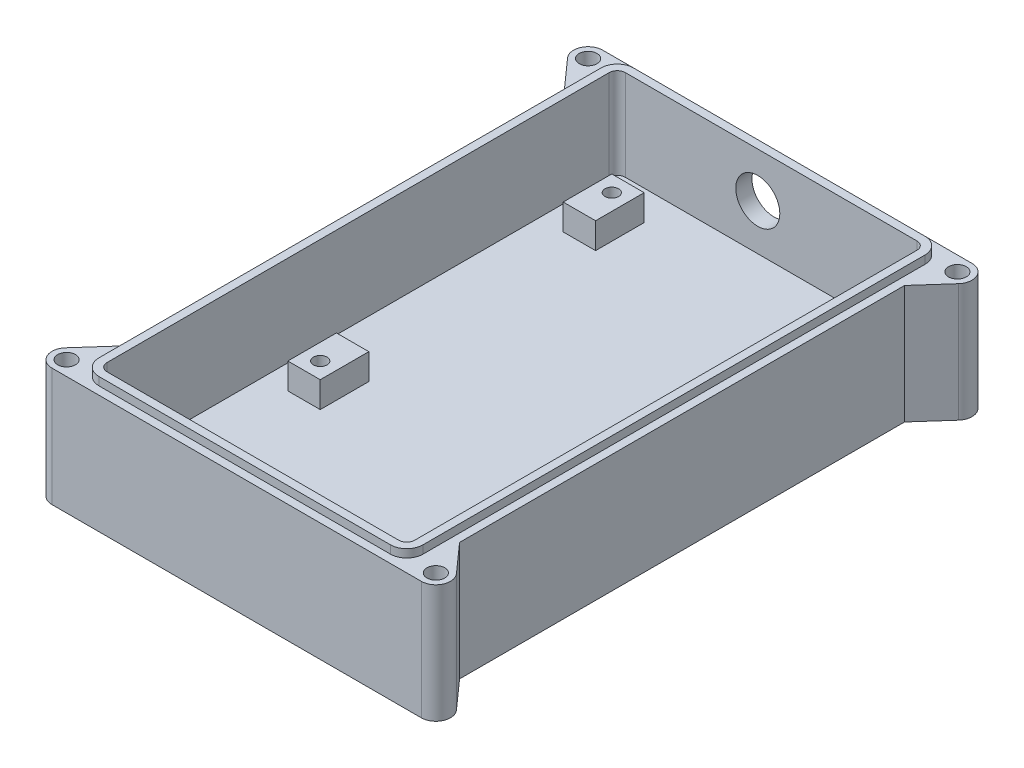
SolidWorks part; units mm, degrees
ref_plane "Alzado" through (0, 0, 0) normal (0, 0, 1) x (1, 0, 0)
ref_plane "Planta" through (0, 0, 0) normal (0, 1, 0) x (1, 0, 0)
ref_plane "Vista lateral" through (0, 0, 0) normal (1, 0, 0) x (0, 0, -1)
sketch "Croquis1" plane through (0, 0, 0) normal (0, 1, 0) x (1, 0, 0)
  line L0 (-45, 80) -> (45, 80)
  line L1 (-47.5, -80) -> (47.5, -80) construction
  line L2 (-47.5, -80) -> (-47.5, 80) construction
  line L3 (-47.5, 80) -> (47.5, 80) construction
  line L4 (47.5, -80) -> (47.5, 80) construction
  line L5 (-47.5, -80) -> (47.5, 80) construction
  line L6 (-47.5, 80) -> (47.5, -80) construction
  line L7 (-47.5, 77.5) -> (-47.5, -77.5)
  line L8 (-45, -80) -> (45, -80)
  line L9 (47.5, -77.5) -> (47.5, 77.5)
  line L10 (-45, 85) -> (45, 85)
  line L11 (52.5, -77.5) -> (52.5, 77.5)
  line L12 (-45, -85) -> (45, -85)
  line L13 (-52.5, 77.5) -> (-52.5, -77.5)
  line L14 (-45, 82.5) -> (45, 82.5)
  line L15 (50, -77.5) -> (50, 77.5)
  line L16 (-45, -82.5) -> (45, -82.5)
  line L17 (-50, 77.5) -> (-50, -77.5)
  circle A0 centre (-45, 77.5) radius 2.5 construction
  circle A1 centre (45, 77.5) radius 2.5 construction
  circle A2 centre (-45, -77.5) radius 2.5 construction
  circle A3 centre (45, -77.5) radius 2.5 construction
  arc A5 (47.5, 77.5) -> (45, 80) centre (45, 77.5) ccw
  arc A6 (-45, 80) -> (-47.5, 77.5) centre (-45, 77.5) ccw
  arc A7 (-47.5, -77.5) -> (-45, -80) centre (-45, -77.5) ccw
  arc A8 (45, -80) -> (47.5, -77.5) centre (45, -77.5) ccw
  arc A9 (52.5, 77.5) -> (45, 85) centre (45, 77.5) ccw
  arc A10 (45, -85) -> (52.5, -77.5) centre (45, -77.5) ccw
  arc A11 (-52.5, -77.5) -> (-45, -85) centre (-45, -77.5) ccw
  arc A12 (-45, 85) -> (-52.5, 77.5) centre (-45, 77.5) ccw
  arc A13 (50, 77.5) -> (45, 82.5) centre (45, 77.5) ccw
  arc A14 (45, -82.5) -> (50, -77.5) centre (45, -77.5) ccw
  arc A15 (-50, -77.5) -> (-45, -82.5) centre (-45, -77.5) ccw
  arc A16 (-45, 82.5) -> (-50, 77.5) centre (-45, 77.5) ccw
  point P0 (0, 0)
  dimension "D3" = 5
  dimension "D4" = 5
  dimension "D5" = 5
  dimension "D6" = 5
  dimension "D1" = 95
  dimension "D2" = 160
  dimension "D7" = 5
  dimension "D8" = 2.5
extrude "Saliente-Extruir2" add sketch "Croquis1" along normal blind 11 contours L8 A8 L9 A5 L0 A6 L7 A7 | L10 A12 L13 A11 L12 A10 L11 A9 A16 L14 A13 L15 A14 L16 A15 L17 | L14 A16 L17 A15 L16 A14 L15 A13 A8 L8 A7 L7 A6 L0 A5 L9
sketch "Croquis2" plane through (0, 11, 0) normal (0, 1, 0) x (1, 0, 0)
  line L4 (45, 85) -> (-45, 85)
  line L5 (-52.5, 77.5) -> (-52.5, -77.5)
  line L6 (-45, -85) -> (45, -85)
  line L7 (52.5, -77.5) -> (52.5, 77.5)
  line L8 (45, 85) -> (-45, 85)
  line L9 (-52.5, 77.5) -> (-52.5, -77.5)
  line L10 (-45, -85) -> (45, -85)
  line L11 (52.5, -77.5) -> (52.5, 77.5)
  line L12 (47.5, -77.5) -> (47.5, 77.5)
  line L13 (-45, -80) -> (45, -80)
  line L14 (-47.5, 77.5) -> (-47.5, -77.5)
  line L15 (45, 80) -> (-45, 80)
  line L16 (47.5, -77.5) -> (47.5, 77.5)
  line L17 (-45, -80) -> (45, -80)
  line L18 (-47.5, 77.5) -> (-47.5, -77.5)
  line L19 (45, 80) -> (-45, 80)
  line L20 (45, 82.5) -> (-45, 82.5)
  line L21 (50, -77.5) -> (50, 77.5)
  line L22 (-45, -82.5) -> (45, -82.5)
  line L23 (-50, 77.5) -> (-50, -77.5)
  line L24 (45, 82.5) -> (-45, 82.5)
  line L25 (50, -77.5) -> (50, 77.5)
  line L26 (-45, -82.5) -> (45, -82.5)
  line L27 (-50, 77.5) -> (-50, -77.5)
  line L28 (45, 85) -> (-45, 85)
  line L29 (52.5, -77.5) -> (52.5, 77.5)
  line L30 (-45, -85) -> (45, -85)
  line L31 (-52.5, 77.5) -> (-52.5, -77.5)
  line L32 (45, 85) -> (-45, 85)
  line L33 (52.5, -77.5) -> (52.5, 77.5)
  line L34 (-45, -85) -> (45, -85)
  line L35 (-52.5, 77.5) -> (-52.5, -77.5)
  arc A4 (-45, 85) -> (-52.5, 77.5) centre (-45, 77.5) ccw
  arc A5 (-52.5, -77.5) -> (-45, -85) centre (-45, -77.5) ccw
  arc A6 (45, -85) -> (52.5, -77.5) centre (45, -77.5) ccw
  arc A7 (52.5, 77.5) -> (45, 85) centre (45, 77.5) ccw
  arc A8 (-45, 85) -> (-52.5, 77.5) centre (-45, 77.5) ccw
  arc A9 (-52.5, -77.5) -> (-45, -85) centre (-45, -77.5) ccw
  arc A10 (45, -85) -> (52.5, -77.5) centre (45, -77.5) ccw
  arc A11 (52.5, 77.5) -> (45, 85) centre (45, 77.5) ccw
  arc A12 (47.5, 77.5) -> (45, 80) centre (45, 77.5) ccw
  arc A13 (45, -80) -> (47.5, -77.5) centre (45, -77.5) ccw
  arc A14 (-47.5, -77.5) -> (-45, -80) centre (-45, -77.5) ccw
  arc A15 (-45, 80) -> (-47.5, 77.5) centre (-45, 77.5) ccw
  arc A16 (47.5, 77.5) -> (45, 80) centre (45, 77.5) ccw
  arc A17 (45, -80) -> (47.5, -77.5) centre (45, -77.5) ccw
  arc A18 (-47.5, -77.5) -> (-45, -80) centre (-45, -77.5) ccw
  arc A19 (-45, 80) -> (-47.5, 77.5) centre (-45, 77.5) ccw
  arc A20 (50, 77.5) -> (45, 82.5) centre (45, 77.5) ccw
  arc A21 (45, -82.5) -> (50, -77.5) centre (45, -77.5) ccw
  arc A22 (-50, -77.5) -> (-45, -82.5) centre (-45, -77.5) ccw
  arc A23 (-45, 82.5) -> (-50, 77.5) centre (-45, 77.5) ccw
  arc A24 (50, 77.5) -> (45, 82.5) centre (45, 77.5) ccw
  arc A25 (45, -82.5) -> (50, -77.5) centre (45, -77.5) ccw
  arc A26 (-50, -77.5) -> (-45, -82.5) centre (-45, -77.5) ccw
  arc A27 (-45, 82.5) -> (-50, 77.5) centre (-45, 77.5) ccw
  arc A28 (-45, 85) -> (-52.5, 77.5) centre (-45, 77.5) ccw
  arc A29 (52.5, 77.5) -> (45, 85) centre (45, 77.5) ccw
  arc A30 (45, -85) -> (52.5, -77.5) centre (45, -77.5) ccw
  arc A31 (-52.5, -77.5) -> (-45, -85) centre (-45, -77.5) ccw
  arc A32 (-45, 85) -> (-52.5, 77.5) centre (-45, 77.5) ccw
  arc A33 (52.5, 77.5) -> (45, 85) centre (45, 77.5) ccw
  arc A34 (45, -85) -> (52.5, -77.5) centre (45, -77.5) ccw
  arc A35 (-52.5, -77.5) -> (-45, -85) centre (-45, -77.5) ccw
  line M33 (45, 85) -> (-45, 85)
  arc M34 (-45, 85) -> (-52.5, 77.5) centre (-45, 77.5) ccw
  line M35 (-52.5, 77.5) -> (-52.5, -77.5)
  arc M36 (-52.5, -77.5) -> (-45, -85) centre (-45, -77.5) ccw
  line M37 (-45, -85) -> (45, -85)
  arc M38 (45, -85) -> (52.5, -77.5) centre (45, -77.5) ccw
  line M39 (52.5, -77.5) -> (52.5, 77.5)
  arc M40 (52.5, 77.5) -> (45, 85) centre (45, 77.5) ccw
  dimension "D1" = 0
  dimension "D2" = 0
  dimension "D3" = 0
  dimension "D4" = 0
extrude "Saliente-Extruir3" add sketch "Croquis2" along normal blind 25.5 contours A27 L24 A24 L25 A25 L26 A26 L27 M40 M33 M34 M35 M36 M37 M38 M39 | L24 A27 L27 A26 L26 A25 L25 A24 A19 L19 A16 L16 A17 L17 A18 L18
sketch "Croquis3" plane through (0, 36.5, 0) normal (0, 1, 0) x (1, 0, 0)
  line L4 (47.5, -77.5) -> (47.5, 77.5)
  line L5 (-45, -80) -> (45, -80)
  line L6 (-47.5, 77.5) -> (-47.5, -77.5)
  line L7 (45, 80) -> (-45, 80)
  line L8 (47.5, -77.5) -> (47.5, 77.5)
  line L9 (-45, -80) -> (45, -80)
  line L10 (-47.5, 77.5) -> (-47.5, -77.5)
  line L11 (45, 80) -> (-45, 80)
  line L12 (45, 82.5) -> (-45, 82.5)
  line L13 (50, -77.5) -> (50, 77.5)
  line L14 (-45, -82.5) -> (45, -82.5)
  line L15 (-50, 77.5) -> (-50, -77.5)
  line L16 (45, 82.5) -> (-45, 82.5)
  line L17 (50, -77.5) -> (50, 77.5)
  line L18 (-45, -82.5) -> (45, -82.5)
  line L19 (-50, 77.5) -> (-50, -77.5)
  line L20 (45, 85) -> (-45, 85)
  line L21 (52.5, -77.5) -> (52.5, 77.5)
  line L22 (-45, -85) -> (45, -85)
  line L23 (-52.5, 77.5) -> (-52.5, -77.5)
  line L24 (45, 85) -> (-45, 85)
  line L25 (52.5, -77.5) -> (52.5, 77.5)
  line L26 (-45, -85) -> (45, -85)
  line L27 (-52.5, 77.5) -> (-52.5, -77.5)
  arc A4 (47.5, 77.5) -> (45, 80) centre (45, 77.5) ccw
  arc A5 (45, -80) -> (47.5, -77.5) centre (45, -77.5) ccw
  arc A6 (-47.5, -77.5) -> (-45, -80) centre (-45, -77.5) ccw
  arc A7 (-45, 80) -> (-47.5, 77.5) centre (-45, 77.5) ccw
  arc A8 (47.5, 77.5) -> (45, 80) centre (45, 77.5) ccw
  arc A9 (45, -80) -> (47.5, -77.5) centre (45, -77.5) ccw
  arc A10 (-47.5, -77.5) -> (-45, -80) centre (-45, -77.5) ccw
  arc A11 (-45, 80) -> (-47.5, 77.5) centre (-45, 77.5) ccw
  arc A12 (50, 77.5) -> (45, 82.5) centre (45, 77.5) ccw
  arc A13 (45, -82.5) -> (50, -77.5) centre (45, -77.5) ccw
  arc A14 (-50, -77.5) -> (-45, -82.5) centre (-45, -77.5) ccw
  arc A15 (-45, 82.5) -> (-50, 77.5) centre (-45, 77.5) ccw
  arc A16 (50, 77.5) -> (45, 82.5) centre (45, 77.5) ccw
  arc A17 (45, -82.5) -> (50, -77.5) centre (45, -77.5) ccw
  arc A18 (-50, -77.5) -> (-45, -82.5) centre (-45, -77.5) ccw
  arc A19 (-45, 82.5) -> (-50, 77.5) centre (-45, 77.5) ccw
  arc A20 (-45, 85) -> (-52.5, 77.5) centre (-45, 77.5) ccw
  arc A21 (52.5, 77.5) -> (45, 85) centre (45, 77.5) ccw
  arc A22 (45, -85) -> (52.5, -77.5) centre (45, -77.5) ccw
  arc A23 (-52.5, -77.5) -> (-45, -85) centre (-45, -77.5) ccw
  arc A24 (-45, 85) -> (-52.5, 77.5) centre (-45, 77.5) ccw
  arc A25 (52.5, 77.5) -> (45, 85) centre (45, 77.5) ccw
  arc A26 (45, -85) -> (52.5, -77.5) centre (45, -77.5) ccw
  arc A27 (-52.5, -77.5) -> (-45, -85) centre (-45, -77.5) ccw
  arc M33 (-47.5, 77.5) -> (-45, 80) centre (-45, 77.5) cw
  line M34 (-45, 80) -> (45, 80)
  arc M35 (45, 80) -> (47.5, 77.5) centre (45, 77.5) cw
  line M36 (47.5, 77.5) -> (47.5, -77.5)
  arc M37 (47.5, -77.5) -> (45, -80) centre (45, -77.5) cw
  line M38 (45, -80) -> (-45, -80)
  arc M39 (-45, -80) -> (-47.5, -77.5) centre (-45, -77.5) cw
  line M40 (-47.5, -77.5) -> (-47.5, 77.5)
  dimension "D1" = 0
  dimension "D2" = 0
  dimension "D3" = 0
extrude "Saliente-Extruir4" add sketch "Croquis3" along normal blind 2.5 contours L16 A19 L19 A18 L18 A17 L17 A16 M40 M33 M34 M35 M36 M37 M38 M39
sketch "Croquis4" plane through (0, 0, 0) normal (0, -1, 0) x (1, 0, 0)
  line L0 (-45, 85) -> (57, 85)
  line L1 (57, 85) -> (-45, 85)
  line L2 (-45, 80) -> (45, 80) construction
  line L3 (52.5, 77.5) -> (52.5, -77.5) construction
  line L4 (47.5, -77.5) -> (47.5, 77.5) construction
  line L5 (-45, 80) -> (45, 80)
  line L6 (52.5, 68.6869) -> (60.3595, 77.5061)
  line L7 (47.5, -77.5) -> (47.5, 77.5)
  line L8 (52.5, 68.6869) -> (48.6887, 68.6869)
  line L9 (48.6887, 68.6869) -> (48.6887, 66.4004)
  line L10 (48.6887, 66.4004) -> (43.3926, 66.4004)
  line L11 (43.3926, 66.4004) -> (43.3926, 85)
  circle A0 centre (57, 80.5) radius 2.75 construction
  circle A1 centre (57, 80.5) radius 4.5
  arc A2 (47.5, 77.5) -> (45, 80) centre (45, 77.5) ccw construction
  arc A3 (47.5, 77.5) -> (45, 80) centre (45, 77.5) ccw
  line M5 (52.5, -77.5) -> (52.5, 77.5)
  arc M6 (52.5, 77.5) -> (45, 85) centre (45, 77.5) ccw
  line M7 (45, 85) -> (-45, 85)
  dimension "D1" = 5.5
  dimension "D2" = 4.5
extrude "Saliente-Extruir5" add sketch "Croquis4" against normal up to surface (36.5 mm away) contours A1 | A1 L0 L6 M6 M5 | L11 L10 L9 L8 M5 M6 M7
mirror "Simetría1" about plane through (0, 0, 0) normal (1, 0, 0) of "Saliente-Extruir5"
mirror "Simetría2" about plane through (0, 0, 0) normal (0, 0, 1) of "Simetría1", "Saliente-Extruir5"
sketch "Croquis6" plane through (0, 11, 0) normal (0, 1, 0) x (1, 0, 0)
  line L0 (0, 65.8) -> (35, 65.8) construction
  line L1 (45, 80) -> (-45, 80) construction
  line L8 (0, -21.45) -> (0, 21.45) construction
  line L14 (-35, 65.8) -> (-35, -24.2) construction
  line L15 (-30, 70.8) -> (-40, 70.8)
  line L16 (-40, -14.2) -> (-30, -14.2)
  line L17 (-40, -14.2) -> (-40, -29.2)
  line L18 (-40, -29.2) -> (-30, -29.2)
  line L19 (-30, -14.2) -> (-30, -29.2)
  line L20 (-40, -14.2) -> (-30, -29.2) construction
  line L21 (-40, -29.2) -> (-30, -14.2) construction
  line L22 (-40, 70.8) -> (-40, 55.8)
  line L23 (-40, 55.8) -> (-30, 55.8)
  line L24 (-30, 55.8) -> (-30, 70.8)
  line L25 (40, -29.2) -> (30, -29.2)
  line L26 (30, -14.2) -> (30, -29.2)
  line L27 (40, -14.2) -> (30, -14.2)
  line L28 (40, -14.2) -> (40, -29.2)
  line L29 (40, 55.8) -> (30, 55.8)
  line L30 (30, 55.8) -> (30, 70.8)
  line L31 (40, 70.8) -> (40, 55.8)
  line L32 (30, 70.8) -> (40, 70.8)
  circle A0 centre (35, 65.8) radius 2.1
  circle A1 centre (-35, 65.8) radius 2.1
  circle A2 centre (-35, -24.2) radius 2.1
  circle A3 centre (35, -24.2) radius 2.1
  point P23 (-35, -21.7)
  dimension "D2" = 4.2
  dimension "D8" = 4.2
  dimension "D12" = 5
  dimension "D1" = 14.2
  dimension "D6" = 35
  dimension "D7" = 90
  dimension "D9" = 10
  dimension "D10" = 15
  dimension "D11" = 5
  dimension "D13" = 15
sketch "Croquis7" plane through (0, 11, 0) normal (0, 1, 0) x (1, 0, 0)
  line L1 (-40.6507, -31.8649) -> (43.0111, -31.8649) construction
  line L2 (-40.6507, -31.8649) -> (-40.6507, -72.8649) construction
  line L3 (-40.6507, -72.8649) -> (43.0111, -72.8649) construction
  line L4 (43.0111, -31.8649) -> (43.0111, -72.8649) construction
  line L5 (-40.6507, -31.8649) -> (43.0111, -72.8649) construction
  line L6 (-40.6507, -72.8649) -> (43.0111, -31.8649) construction
  point P4 (1.1802, -52.3649)
  dimension "D1" = 41
extrude "Saliente-Extruir6" add sketch "Croquis6" along normal blind 8
sketch "Croquis8" plane through (0, 0, -85) normal (0, 0, -1) x (-1, 0, 0)
  line L1 (45, 11) -> (-45, 11) construction
  line L2 (45, 11) -> (-45, 11) construction
  line L3 (4.13, 11) -> (4.13, 25.14) construction
  line L4 (57, 0) -> (57, 36.5)
  line L5 (57, 36.5) -> (-57, 36.5)
  line L6 (-57, 36.5) -> (-57, 0)
  line L7 (-57, 0) -> (57, 0)
  line L8 (57, 0) -> (57, 36.5)
  line L9 (57, 36.5) -> (-57, 36.5)
  line L10 (-57, 36.5) -> (-57, 0)
  line L11 (-57, 0) -> (57, 0)
  line L12 (61.5, 0) -> (61.5, 36.5) construction
  line L13 (61.5, 0) -> (61.5, 36.5)
  circle A0 centre (4.13, 25.14) radius 6.8
  dimension "D4" = 13.6
  dimension "D2" = 14.14
  dimension "D3" = 57.37
  dimension "D1" = 0
extrude "Cortar-Extruir2" cut sketch "Croquis8" against normal blind 8 contours A0
sketch "Croquis9" plane through (47.5, 0, 0) normal (-1, 0, 0) x (0, 0, 1)
  line L0 (68.6869, 0) -> (-68.6869, 0) construction
  circle A0 centre (0, 22) radius 6.5
  dimension "D1" = 13
  dimension "D2" = 22
extrude "Cortar-Extruir3" cut sketch "Croquis9" against normal blind 8
sketch "Croquis11" plane through (0, 0, 0) normal (0, -1, 0) x (1, 0, 0)
  line L0 (-52.5, -68.6869) -> (-52.5, 68.6869) construction
  line L1 (-47.5, -19) -> (-17.5, -19)
  line L2 (-47.5, -19) -> (-47.5, 19)
  line L3 (-47.5, 19) -> (-17.5, 19)
  line L4 (-17.5, -19) -> (-17.5, 19)
  line L5 (-47.5, -19) -> (-17.5, 19) construction
  line L6 (-47.5, 19) -> (-17.5, -19) construction
  line L7 (-22.5, 19) -> (-22.5, -19)
  line L8 (-42.5, 19) -> (-42.5, -19)
  point P0 (-32.5, 0)
  point P7 (-17.5, 0)
  dimension "D1" = 30
  dimension "D2" = 38
  dimension "D3" = 5
  dimension "D4" = 5
  dimension "D5" = 5
ref_plane "Plano1" through (0, 0, 19) normal (0, 0, 1) x (1, 0, 0)
sketch "Croquis12" plane through (0, 0, 19) normal (0, 0, 1) x (1, 0, 0)
  line L0 (-32.5, 0) -> (-32.5, -13.3436) construction
  line L1 (-47.5, 0) -> (-17.5, 0) construction
  line L2 (-47.5, 0) -> (-17.5, 0)
  line L3 (-42.5378, 0) -> (-22.4994, 0)
  circle A0 centre (-32.5, -7.0013) radius 16.5535
  circle A2 centre (-32.5, -7.0013) radius 12.2078
extrude "Cortar-Extruir4" cut sketch "Croquis12" against normal blind 38 contours A2 L2 A0 | A2 L2 A0
mirror "Simetría5" about plane through (0, 0, 0) normal (1, 0, 0) of "Cortar-Extruir4"
sketch "Croquis13" plane through (0, 36.5, 0) normal (0, 1, 0) x (1, 0, 0)
  arc A0 (60.3595, 77.5061) -> (57, 85) centre (57, 80.5) ccw construction
  arc A1 (60.3595, 77.5061) -> (57, 85) centre (57, 80.5) ccw
  circle A2 centre (57, 80.5) radius 2.75
  dimension "D1" = 5.5
extrude "Cortar-Extruir5" cut sketch "Croquis13" against normal blind 12.5 contours A2
mirror "Simetría6" about plane through (0, 0, 0) normal (0, 0, 1) of "Cortar-Extruir5"
mirror "Simetría7" about plane through (0, 0, 0) normal (1, 0, 0) of "Simetría6", "Cortar-Extruir5"
sketch "Croquis15" plane through (52.5, 0, 0) normal (1, 0, 0) x (0, 0, -1)
  line L4 (68.6869, 0) -> (68.6869, 36.5)
  line L5 (68.6869, 36.5) -> (-68.6869, 36.5)
  line L6 (-68.6869, 36.5) -> (-68.6869, 0)
  line L7 (-68.6869, 0) -> (68.6869, 0)
  line L8 (68.6869, 0) -> (68.6869, 36.5)
  line L9 (68.6869, 36.5) -> (-68.6869, 36.5)
  line L10 (-68.6869, 36.5) -> (-68.6869, 0)
  line L11 (-68.6869, 0) -> (68.6869, 0)
  circle A0 centre (0, 22) radius 6.5 construction
  circle A1 centre (0, 22) radius 6.5
  circle A2 centre (0, 22) radius 12.5
  circle M13 centre (0, 22) radius 6.5
  dimension "D2" = 25
  dimension "D1" = 0
extrude "Cortar-Extruir6" cut sketch "Croquis15" against normal blind 2.5 contours A2 M13
sketch "Croquis16" plane through (52.5, 0, 0) normal (1, 0, 0) x (0, 0, -1)
  circle A0 centre (0, 22) radius 13.4133
extrude "Saliente-Extruir7" add sketch "Croquis16" against normal up to surface (5 mm away) up to face at (47.5, 22, 6.5)
